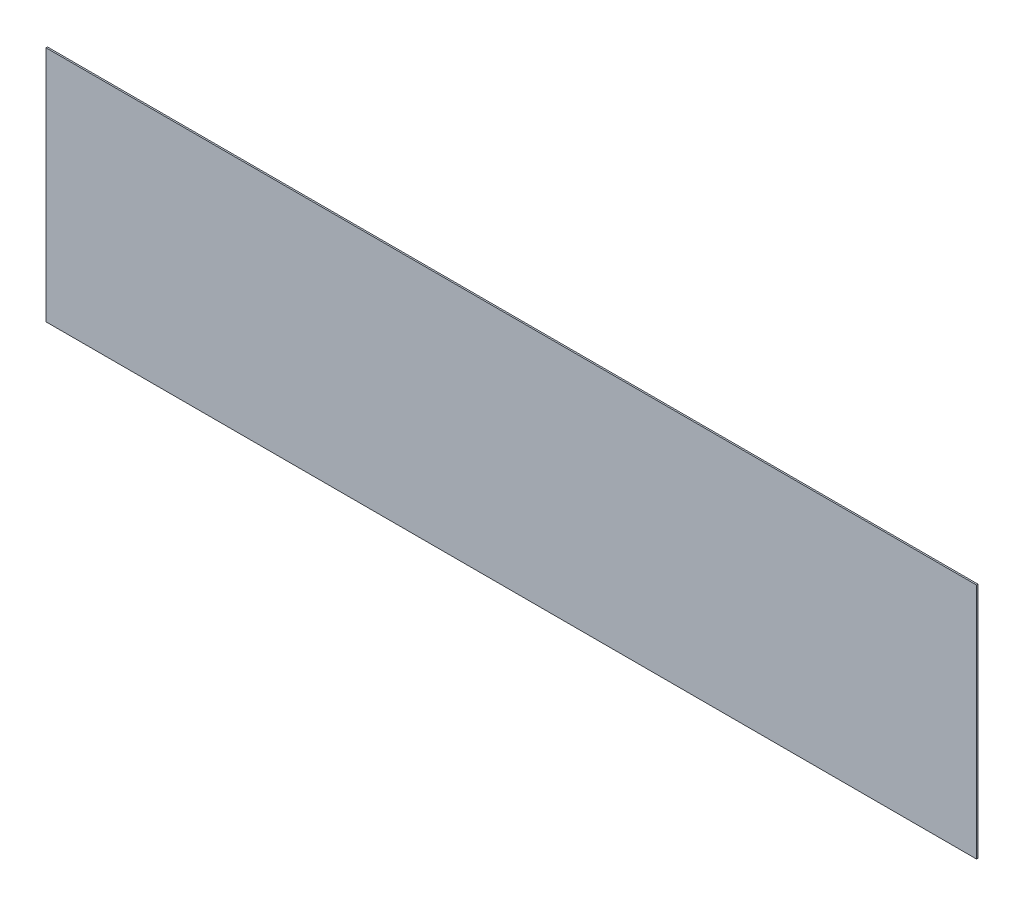
SolidWorks part; units mm, degrees
material "6061 Alloy"
ref_plane "Front Plane" through (0, 0, 0) normal (0, 0, 1) x (1, 0, 0)
ref_plane "Top Plane" through (0, 0, 0) normal (0, 1, 0) x (1, 0, 0)
ref_plane "Right Plane" through (0, 0, 0) normal (1, 0, 0) x (0, 0, -1)
sketch "Sketch1" plane through (0, 0, 0) normal (0, 0, 1) x (1, 0, 0)
  line L1 (0, 0) -> (321.5, 0)
  line L2 (0, 0) -> (0, 82)
  line L3 (0, 82) -> (321.5, 82)
  line L4 (321.5, 0) -> (321.5, 82)
  dimension "D1" = 82
  dimension "D2" = 321.5
extrude "Sheet" add sketch "Sketch1" along normal blind 0.511
